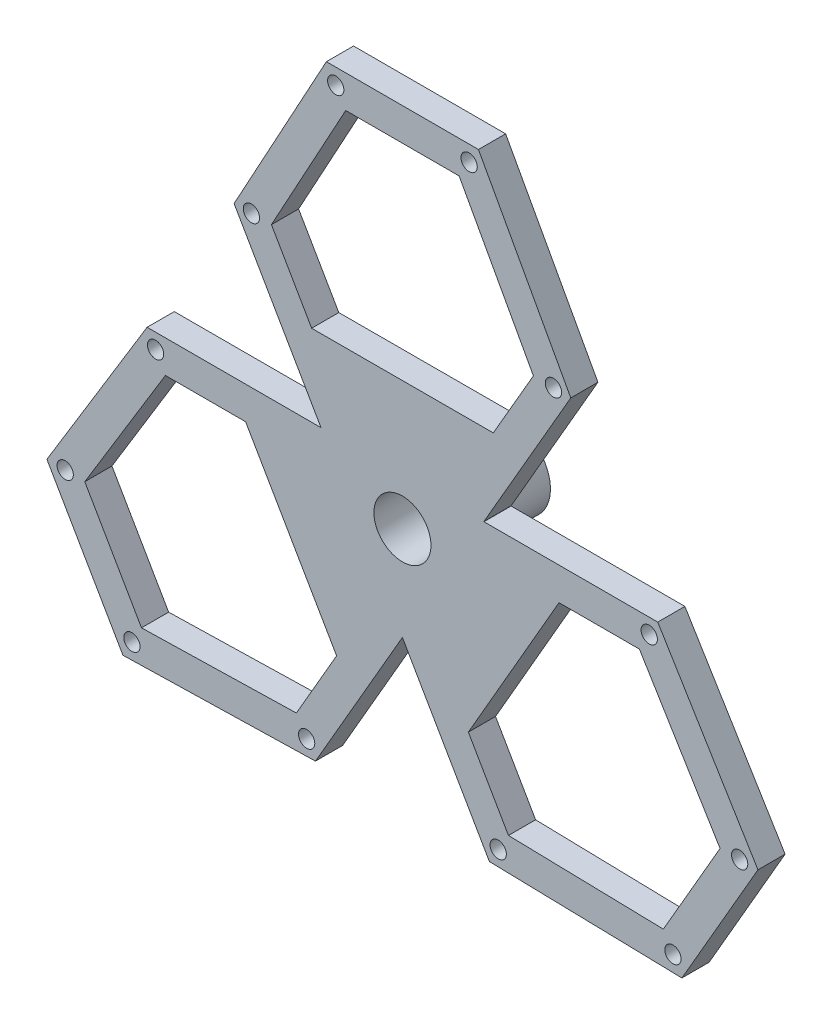
SolidWorks part; units mm, degrees
ref_plane "Front Plane" through (0, 0, 0) normal (0, 0, 1) x (1, 0, 0)
ref_plane "Top Plane" through (0, 0, 0) normal (0, 1, 0) x (1, 0, 0)
ref_plane "Right Plane" through (0, 0, 0) normal (1, 0, 0) x (0, 0, -1)
sketch "Sketch1" plane through (0, 0, 0) normal (0, 0, 1) x (1, 0, 0)
  line L0 (0, 17.3205) -> (0, 67.5) construction
  line L1 (15, 8.6603) -> (10, 17.3205) construction
  line L2 (0, 17.3205) -> (-10, 17.3205) construction
  line L3 (-15, 8.6603) -> (-20, 0) construction
  line L4 (-20, 0) -> (-15, -8.6603) construction
  line L5 (-10, -17.3205) -> (0, -17.3205) construction
  line L6 (15, -8.6603) -> (20, 0) construction
  line L7 (77.9423, 0) -> (38.9711, 67.5) construction
  line L8 (38.9711, 67.5) -> (-38.9711, 67.5) construction
  line L9 (-38.9711, 67.5) -> (-77.9423, 0) construction
  line L10 (-77.9423, 0) -> (-38.9711, -67.5) construction
  line L11 (-38.9711, -67.5) -> (38.9711, -67.5) construction
  line L12 (38.9711, -67.5) -> (77.9423, 0) construction
  line L14 (-30.995, 36.3817) -> (-14, 67.5)
  line L18 (10, 17.3205) -> (0, 17.3205) construction
  line L19 (-15, -8.6603) -> (-10, -17.3205) construction
  line L20 (10, -17.3205) -> (15, -8.6603) construction
  line L21 (-10, 17.3205) -> (-15, 8.6603) construction
  line L22 (20, 0) -> (15, 8.6603) construction
  line L23 (0, -17.3205) -> (10, -17.3205) construction
  line L24 (-10, 17.3205) -> (-14.995, 8.6689) construction
  line L25 (-15, 8.6603) -> (-14.995, 8.6689)
  line L26 (-14.995, 8.6689) -> (-30.995, 36.3817)
  line L27 (14, 67.5) -> (-14, 67.5)
  line L28 (30.995, 36.3817) -> (14, 67.5)
  line L29 (14.995, 8.6689) -> (30.995, 36.3817)
  line L30 (15, 8.6603) -> (14.995, 8.6689)
  line L31 (15, 8.6603) -> (15.005, 8.6516)
  line L32 (15.005, 8.6516) -> (47.005, 8.6516)
  line L33 (47.005, 8.6516) -> (65.4567, -21.6256)
  line L34 (51.4567, -45.8744) -> (65.4567, -21.6256)
  line L35 (16.01, -45.0333) -> (51.4567, -45.8744)
  line L36 (0.01, -17.3205) -> (16.01, -45.0333)
  line L37 (0, -17.3205) -> (0.01, -17.3205)
  line L38 (0, -17.3205) -> (-0.01, -17.3205)
  line L39 (-0.01, -17.3205) -> (-16.01, -45.0333)
  line L40 (-16.01, -45.0333) -> (-51.4567, -45.8744)
  line L41 (-65.4567, -21.6256) -> (-51.4567, -45.8744)
  line L42 (-47.005, 8.6516) -> (-65.4567, -21.6256)
  line L43 (-15.005, 8.6516) -> (-47.005, 8.6516)
  line L44 (-15, 8.6603) -> (-15.005, 8.6516)
  arc A0 (15, 8.6603) -> (0, 17.3205) centre (0, 0) ccw construction
  circle A1 centre (0, 0) radius 67.5 construction
  arc A2 (15, -8.6603) -> (15, 8.6603) centre (0, 0) ccw construction
  arc A3 (0, -17.3205) -> (15, -8.6603) centre (0, 0) ccw construction
  arc A4 (0, 17.3205) -> (-15, 8.6603) centre (0, 0) ccw construction
  arc A5 (-15, -8.6603) -> (0, -17.3205) centre (0, 0) ccw construction
  arc A6 (-15, 8.6603) -> (-15, -8.6603) centre (0, 0) ccw construction
  point P47 (0, 0)
  dimension "D1" = 20
  dimension "D2" = 135
  dimension "D3" = 14
  dimension "D4" = 9.99
  dimension "D5" = 32
  dimension "D6" = 120
  dimension "D7" = 3
extrude "Boss-Extrude1" add sketch "Sketch1" along normal blind 5
sketch "Sketch2" plane through (0, 0, 5) normal (0, 0, 1) x (1, 0, 0)
  line L0 (-15.005, 8.6516) -> (0.01, -17.3205) construction
  line L1 (-20.4956, -11.8211) -> (-7.4975, -4.3345) construction
  line L2 (-15.005, 8.6516) -> (15.005, 8.6516) construction
  line L3 (15.005, 8.6516) -> (0.01, -17.3205) construction
  line L5 (-28.8721, 2.6516) -> (-12.119, -26.2939)
  line L20 (-19.5212, -39.1149) -> (-5.2062, -14.3205)
  line L21 (-48.0404, -39.7916) -> (-19.5212, -39.1149)
  line L22 (-58.4807, -21.7084) -> (-48.0404, -39.7916)
  line L23 (-43.6351, 2.6516) -> (-58.4807, -21.7084)
  line L24 (-15.005, 2.6516) -> (-43.6351, 2.6516)
  line L25 (-19.5212, -39.1149) -> (-12.119, -26.2939)
  line L26 (-48.0404, -39.7916) -> (-19.5212, -39.1149)
  line L27 (-58.4807, -21.7084) -> (-48.0404, -39.7916)
  line L28 (-43.6351, 2.6516) -> (-58.4807, -21.7084)
  line L29 (-28.8721, 2.6516) -> (-43.6351, 2.6516)
  line L31 (-24.1139, 36.4633) -> (-16.7117, 23.6423)
  line L32 (16.7324, 23.6782) -> (-16.7117, 23.6423)
  line L33 (16.7324, 23.6782) -> (24.1139, 36.4633)
  line L34 (24.1139, 36.4633) -> (10.4404, 61.5)
  line L35 (10.4404, 61.5) -> (-10.4404, 61.5)
  line L36 (-10.4404, 61.5) -> (-24.1139, 36.4633)
  line L37 (43.6351, 2.6516) -> (28.8306, 2.6516)
  line L38 (12.1397, -26.3298) -> (28.8306, 2.6516)
  line L39 (12.1397, -26.3298) -> (19.5212, -39.1149)
  line L40 (19.5212, -39.1149) -> (48.0404, -39.7916)
  line L41 (48.0404, -39.7916) -> (58.4807, -21.7084)
  line L42 (58.4807, -21.7084) -> (43.6351, 2.6516)
  point P31 (0, -1.1576)
  point P32 (0, 0)
  dimension "D2" = 15
  dimension "D1" = 6
  dimension "D3" = 3
extrude "Cut-Extrude1" cut sketch "Sketch2" against normal through all
sketch "Sketch5" plane through (0, 0, 5) normal (0, 0, 1) x (1, 0, 0)
  line L0 (-47.005, 8.6516) -> (-43.8811, 3.0895) construction
  line L1 (-65.4567, -21.6256) -> (-58.7141, -21.7056) construction
  line L2 (-51.4567, -45.8744) -> (-48.1547, -39.9951) construction
  line L3 (-16.01, -45.0333) -> (-19.265, -39.5469) construction
  line L4 (30.995, 36.3817) -> (24.6161, 36.4574) construction
  line L5 (14, 67.5) -> (10.5594, 61.7007) construction
  line L6 (-14, 67.5) -> (-10.5594, 61.7007) construction
  line L7 (-30.995, 36.3817) -> (-24.6161, 36.4574) construction
  line L8 (16.01, -45.0333) -> (19.265, -39.5469) construction
  line L9 (51.4567, -45.8744) -> (48.1547, -39.9951) construction
  line L10 (65.4567, -21.6256) -> (58.7141, -21.7056) construction
  line L11 (47.005, 8.6516) -> (43.8811, 3.0895) construction
  circle A0 centre (-45.443, 5.8705) radius 1.5
  circle A1 centre (-62.0854, -21.6656) radius 1.5
  circle A2 centre (-49.8057, -42.9347) radius 1.5
  circle A3 centre (-17.6375, -42.2901) radius 1.5
  circle A4 centre (27.8056, 36.4196) radius 1.5
  circle A5 centre (12.2797, 64.6003) radius 1.5
  circle A6 centre (-12.2797, 64.6003) radius 1.5
  circle A7 centre (-27.8056, 36.4196) radius 1.5
  circle A8 centre (17.6375, -42.2901) radius 1.5
  circle A9 centre (49.8057, -42.9347) radius 1.5
  circle A10 centre (62.0854, -21.6656) radius 1.5
  circle A11 centre (45.443, 5.8705) radius 1.5
  point P48 (0, 0)
  point P49 (0, 0)
  dimension "D1" = 3
sketch "Sketch6" plane through (0, 0, 0) normal (0, 0, -1) x (-1, 0, 0)
  circle A0 centre (0, 0) radius 7.25
  dimension "D1" = 14.5
extrude "Boss-Extrude3" add sketch "Sketch6" along normal blind 15 contours A0
sketch "Sketch3" plane through (0, 0, -15) normal (0, 0, -1) x (-1, 0, 0)
  circle A0 centre (0, 0) radius 5.25
  dimension "D1" = 10.5
extrude "Cut-Extrude2" cut sketch "Sketch3" against normal up to surface (20 mm away) up to face at (35.108, -20.2736, 5)
extrude "Cut-Extrude3" cut sketch "Sketch5" against normal up to surface (5 mm away) up to face at (7.25, 0, 0)
sketch "Sketch8" plane through (0, 0, 0) normal (0, 0, -1) x (-1, 0, 0)
  circle A0 centre (0, 0) radius 11
  circle A1 centre (0, 0) radius 7.25
  dimension "D1" = 22
extrude "Cut-Extrude4" cut sketch "Sketch8" against normal blind 2.5
